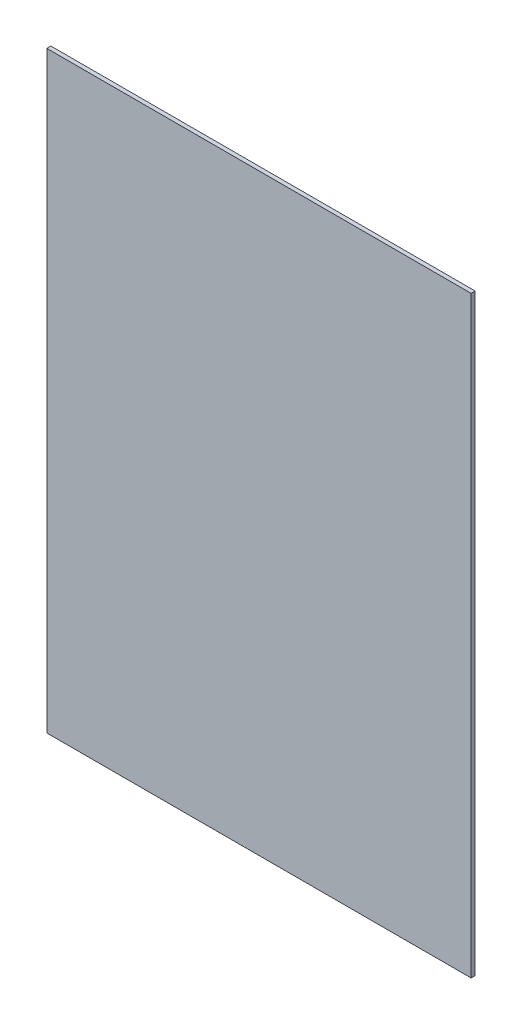
SolidWorks part; units mm, degrees
ref_plane "Plan de face" through (0, 0, 0) normal (0, 0, 1) x (1, 0, 0)
ref_plane "Plan de dessus" through (0, 0, 0) normal (0, 1, 0) x (1, 0, 0)
ref_plane "Plan de droite" through (0, 0, 0) normal (1, 0, 0) x (0, 0, -1)
sketch "Esquisse1" plane through (0, 0, 0) normal (0, 0, 1) x (1, 0, 0)
  line L1 (-340, -475) -> (340, -475)
  line L2 (-340, -475) -> (-340, 475)
  line L3 (-340, 475) -> (340, 475)
  line L4 (340, -475) -> (340, 475)
  line L5 (-340, -475) -> (340, 475) construction
  line L6 (-340, 475) -> (340, -475) construction
  point P0 (0, 0)
  dimension "D1" = 950
  dimension "D2" = 680
extrude "Boss.-Extru.1" add sketch "Esquisse1" along normal blind 6.5
